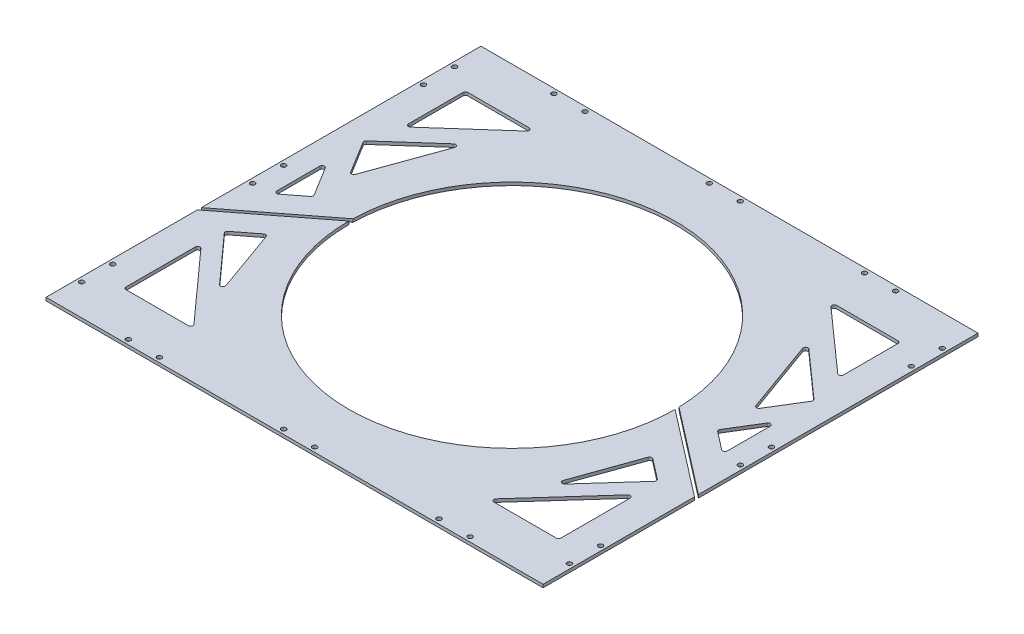
SolidWorks part; units mm, degrees
material "Thornel Mat VMA"
ref_plane "前视基准面" through (0, 0, 0) normal (0, 0, 1) x (1, 0, 0)
ref_plane "上视基准面" through (0, 0, 0) normal (0, 1, 0) x (1, 0, 0)
ref_plane "右视基准面" through (0, 0, 0) normal (1, 0, 0) x (0, 0, -1)
sketch "草图1" plane through (0, 0, 0) normal (0, 1, 0) x (1, 0, 0)
  line L0 (160, 280) -> (160, 0) construction
  line L1 (0, 0) -> (320, 0)
  line L2 (0, 0) -> (0, 280)
  line L3 (0, 280) -> (320, 280)
  line L4 (320, 0) -> (320, 280)
  circle A0 centre (160, 140) radius 105
  dimension "D3" = 210
  dimension "D1" = 280
  dimension "D2" = 320
extrude "凸台-拉伸1" add sketch "草图1" along normal blind 2
sketch "草图2" plane through (0, 2, 0) normal (0, 1, 0) x (1, 0, 0)
  line L0 (55, 140) -> (0, 97.4718)
  line L1 (0, 280) -> (0, 0) construction
  line L2 (0, 97.4718) -> (0, 100)
  line L3 (0, 100) -> (55.031, 142.5521)
  line L4 (160, 280) -> (160, 0) construction
  line L5 (320, 280) -> (0, 280) construction
  line L6 (0, 0) -> (320, 0) construction
  line L7 (320, 100) -> (264.969, 142.5521)
  line L8 (320, 97.4718) -> (320, 100)
  line L9 (265, 140) -> (320, 97.4718)
  circle A0 centre (160, 140) radius 105 construction
  arc A1 (55.031, 142.5521) -> (55, 140) centre (160, 140) ccw
  arc A2 (264.969, 142.5521) -> (265, 140) centre (160, 140) cw
  dimension "D1" = 2
  dimension "D2" = 40
extrude "切除-拉伸1" cut sketch "草图2" against normal through all
sketch "草图3" plane through (0, 2, 0) normal (0, 1, 0) x (1, 0, 0)
  line L0 (3, 40) -> (3, 20) construction
  line L1 (160, 280) -> (160, 0) construction
  line L2 (320, 280) -> (0, 280) construction
  line L3 (0, 0) -> (320, 0) construction
  line L4 (0, 97.4718) -> (0, 0) construction
  line L5 (50, 3) -> (70, 3) construction
  line L6 (160, 140) -> (0, 140) construction
  line L7 (0, 280) -> (0, 100) construction
  line L8 (50, 277) -> (70, 277) construction
  line L9 (3, 240) -> (3, 260) construction
  line L10 (317, 240) -> (317, 260) construction
  line L11 (270, 277) -> (250, 277) construction
  line L12 (270, 3) -> (250, 3) construction
  line L13 (317, 40) -> (317, 20) construction
  line L14 (3, 150) -> (3, 130) construction
  line L15 (317, 150) -> (317, 130) construction
  line L16 (150, 3) -> (170, 3) construction
  line L17 (150, 277) -> (170, 277) construction
  circle A0 centre (3, 40) radius 1.5
  circle A1 centre (3, 20) radius 1.5
  circle A2 centre (50, 3) radius 1.5
  circle A3 centre (70, 3) radius 1.5
  circle A4 centre (70, 277) radius 1.5
  circle A5 centre (50, 277) radius 1.5
  circle A6 centre (3, 260) radius 1.5
  circle A7 centre (3, 240) radius 1.5
  circle A8 centre (317, 240) radius 1.5
  circle A9 centre (317, 260) radius 1.5
  circle A10 centre (270, 277) radius 1.5
  circle A11 centre (250, 277) radius 1.5
  circle A12 centre (250, 3) radius 1.5
  circle A13 centre (270, 3) radius 1.5
  circle A14 centre (317, 20) radius 1.5
  circle A15 centre (317, 40) radius 1.5
  circle A16 centre (3, 150) radius 1.5
  circle A17 centre (3, 130) radius 1.5
  circle A18 centre (317, 130) radius 1.5
  circle A19 centre (317, 150) radius 1.5
  circle A20 centre (150, 3) radius 1.5
  circle A21 centre (170, 3) radius 1.5
  circle A22 centre (170, 277) radius 1.5
  circle A23 centre (150, 277) radius 1.5
  point P46 (3, 140)
  point P55 (160, 3)
  dimension "D1" = 20
  dimension "D3" = 3
  dimension "D5" = 20
  dimension "D7" = 3
  dimension "D9" = 3
  dimension "D12" = 3
  dimension "D2" = 3
  dimension "D4" = 20
  dimension "D6" = 50
  dimension "D8" = 3
  dimension "D10" = 20
  dimension "D11" = 20
extrude "切除-拉伸2" cut sketch "草图3" against normal through all
sketch "草图4" plane through (0, 2, 0) normal (0, 1, 0) x (1, 0, 0)
  line L0 (20, 248.5) -> (20, 213.3403)
  line L1 (22.4965, 212.2192) -> (62.0512, 247.3789)
  line L2 (61.0547, 250) -> (21.5, 250)
  line L3 (0, 280) -> (0, 100) construction
  line L4 (320, 280) -> (0, 280) construction
  line L5 (45.595, 216.6957) -> (15.9396, 190.3353)
  line L6 (15.658, 188.429) -> (28.3675, 167.7407)
  line L7 (31.0568, 168.0176) -> (48.0028, 215.0663)
  line L8 (15, 161.2678) -> (15, 133.6158)
  line L9 (17.4176, 132.4291) -> (28.9343, 141.3344)
  line L10 (29.2949, 143.3062) -> (17.7781, 162.053)
  line L11 (55.031, 142.5521) -> (0, 100) construction
  line L12 (20, 76.0911) -> (20, 31.5)
  line L13 (21.5, 30) -> (61.632, 30)
  line L14 (62.7469, 32.5034) -> (22.6149, 77.0945)
  line L15 (0, 0) -> (320, 0) construction
  line L16 (34.7026, 105.3441) -> (21.795, 95.3634)
  line L17 (21.5976, 93.1733) -> (48.8852, 62.8538)
  line L18 (51.4129, 64.3614) -> (37.033, 104.6616)
  line L19 (0, 97.4718) -> (55, 140) construction
  line L20 (160, 280) -> (160, 0) construction
  line L21 (268.5871, 64.3614) -> (282.967, 104.6616)
  line L22 (298.4024, 93.1733) -> (271.1148, 62.8538)
  line L23 (285.2974, 105.3441) -> (298.205, 95.3634)
  line L24 (257.2531, 32.5034) -> (297.3851, 77.0945)
  line L25 (298.5, 30) -> (258.368, 30)
  line L26 (300, 76.0911) -> (300, 31.5)
  line L27 (290.7051, 143.3062) -> (302.2219, 162.053)
  line L28 (302.5824, 132.4291) -> (291.0657, 141.3344)
  line L29 (305, 161.2678) -> (305, 133.6158)
  line L30 (288.9432, 168.0176) -> (271.9972, 215.0663)
  line L31 (304.342, 188.429) -> (291.6325, 167.7407)
  line L32 (274.405, 216.6957) -> (304.0604, 190.3353)
  line L33 (258.9453, 250) -> (298.5, 250)
  line L34 (297.5035, 212.2192) -> (257.9488, 247.3789)
  line L35 (300, 248.5) -> (300, 213.3403)
  arc A0 (15, 133.6158) -> (17.4176, 132.4291) centre (16.5, 133.6158) ccw
  arc A1 (28.9343, 141.3344) -> (29.2949, 143.3062) centre (28.0168, 142.521) ccw
  arc A2 (15, 161.2678) -> (17.7781, 162.053) centre (16.5, 161.2678) cw
  arc A3 (15.9396, 190.3353) -> (15.658, 188.429) centre (16.9361, 189.2141) ccw
  arc A4 (28.3675, 167.7407) -> (31.0568, 168.0176) centre (29.6456, 168.5259) ccw
  arc A5 (45.595, 216.6957) -> (48.0028, 215.0663) centre (46.5916, 215.5746) cw
  arc A6 (20, 213.3403) -> (22.4965, 212.2192) centre (21.5, 213.3403) ccw
  arc A7 (62.0512, 247.3789) -> (61.0547, 250) centre (61.0547, 248.5) ccw
  arc A8 (20, 248.5) -> (21.5, 250) centre (21.5, 248.5) cw
  arc A9 (61.632, 30) -> (62.7469, 32.5034) centre (61.632, 31.5) ccw
  arc A10 (20, 31.5) -> (21.5, 30) centre (21.5, 31.5) ccw
  arc A11 (20, 76.0911) -> (22.6149, 77.0945) centre (21.5, 76.0911) cw
  arc A12 (48.8852, 62.8538) -> (51.4129, 64.3614) centre (50.0001, 63.8573) ccw
  arc A13 (21.795, 95.3634) -> (21.5976, 93.1733) centre (22.7126, 94.1768) ccw
  arc A14 (34.7026, 105.3441) -> (37.033, 104.6616) centre (35.6202, 104.1575) cw
  arc A15 (285.2974, 105.3441) -> (282.967, 104.6616) centre (284.3798, 104.1575) ccw
  arc A16 (298.205, 95.3634) -> (298.4024, 93.1733) centre (297.2874, 94.1768) cw
  arc A17 (271.1148, 62.8538) -> (268.5871, 64.3614) centre (269.9999, 63.8573) cw
  arc A18 (300, 76.0911) -> (297.3851, 77.0945) centre (298.5, 76.0911) ccw
  arc A19 (300, 31.5) -> (298.5, 30) centre (298.5, 31.5) cw
  arc A20 (258.368, 30) -> (257.2531, 32.5034) centre (258.368, 31.5) cw
  arc A21 (300, 248.5) -> (298.5, 250) centre (298.5, 248.5) ccw
  arc A22 (257.9488, 247.3789) -> (258.9453, 250) centre (258.9453, 248.5) cw
  arc A23 (300, 213.3403) -> (297.5035, 212.2192) centre (298.5, 213.3403) cw
  arc A24 (274.405, 216.6957) -> (271.9972, 215.0663) centre (273.4084, 215.5746) ccw
  arc A25 (291.6325, 167.7407) -> (288.9432, 168.0176) centre (290.3544, 168.5259) cw
  arc A26 (304.0604, 190.3353) -> (304.342, 188.429) centre (303.0639, 189.2141) cw
  arc A27 (305, 161.2678) -> (302.2219, 162.053) centre (303.5, 161.2678) ccw
  arc A28 (291.0657, 141.3344) -> (290.7051, 143.3062) centre (291.9832, 142.521) cw
  arc A29 (305, 133.6158) -> (302.5824, 132.4291) centre (303.5, 133.6158) cw
  point P25 (30, 142.1584)
  point P30 (15, 189.5001)
  point P33 (30, 165.0833)
  point P36 (50, 220.6112)
  point P39 (20, 210)
  point P42 (65, 250)
  point P45 (20, 250)
  point P52 (65, 30)
  point P55 (20, 30)
  point P58 (20, 80)
  point P61 (53.9646, 57.21)
  point P64 (20.5164, 94.3747)
  point P67 (36.3382, 106.6087)
  point P115 (283.6618, 106.6087)
  point P116 (299.4836, 94.3747)
  point P117 (266.0354, 57.21)
  point P118 (300, 80)
  point P119 (300, 30)
  point P120 (255, 30)
  point P121 (300, 250)
  point P122 (255, 250)
  point P123 (300, 210)
  point P124 (270, 220.6112)
  point P125 (290, 165.0833)
  point P126 (305, 189.5001)
  point P127 (290, 142.1584)
  dimension "D12" = 1.5
  dimension "D20" = 1.5
  dimension "D1" = 20
  dimension "D2" = 30
  dimension "D3" = 40
  dimension "D4" = 45
  dimension "D5" = 15
  dimension "D6" = 15
  dimension "D7" = 12
  dimension "D8" = 12
  dimension "D9" = 15
  dimension "D10" = 35
  dimension "D11" = 15
  dimension "D13" = 30
  dimension "D14" = 45
  dimension "D15" = 50
  dimension "D16" = 10
  dimension "D17" = 15
  dimension "D18" = 20
  dimension "D19" = 50
extrude "切除-拉伸3" cut sketch "草图4" against normal through all
